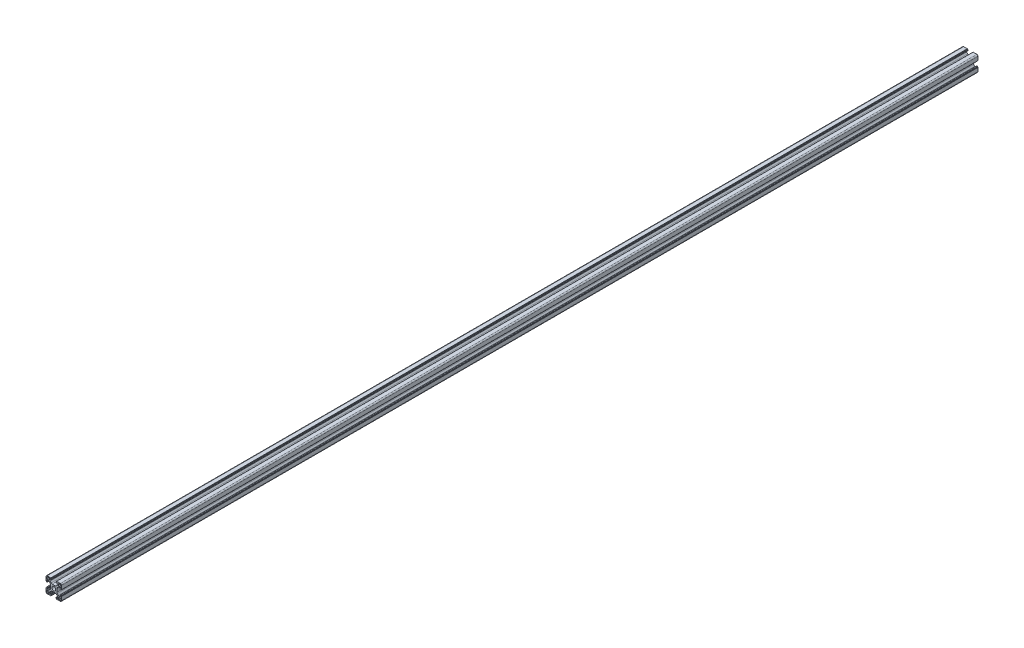
SolidWorks part; units mm, degrees
ref_plane "Спереди" through (0, 0, 0) normal (0, 0, 1) x (1, 0, 0)
ref_plane "Сверху" through (0, 0, 0) normal (0, 1, 0) x (1, 0, 0)
ref_plane "Справа" through (0, 0, 0) normal (1, 0, 0) x (0, 0, -1)
sketch "Эскиз1" plane through (0, 0, 0) normal (0, 0, 1) x (1, 0, 0)
  line L0 (-25.8933, 69.2728) -> (-28.8933, 66.2728) construction
  line L1 (-34.9933, 64.1728) -> (-33.0945, 64.1728)
  line L2 (-34.9933, 60.1728) -> (-24.9933, 70.1728) construction
  line L3 (-27.3933, 67.7728) -> (-28.8933, 69.2728) construction
  line L4 (-31.6803, 64.7586) -> (-30.3791, 66.0598)
  line L5 (-28.0933, 66.2728) -> (-26.6933, 66.2728)
  line L6 (-28.8933, 67.0728) -> (-28.8933, 68.4728)
  line L7 (-26.6933, 69.2728) -> (-28.0933, 69.2728)
  line L8 (-29.7933, 68.3728) -> (-29.7933, 67.474)
  line L9 (-31.2301, 68.246) -> (-30.7498, 68.7264)
  line L10 (-31.7933, 69.7219) -> (-31.2933, 69.7219)
  line L11 (-31.4069, 68.1728) -> (-31.6933, 68.1728)
  line L12 (-30.3962, 68.8728) -> (-30.2933, 68.8728)
  line L13 (-31.2933, 70.0228) -> (-31.2933, 69.7219)
  line L14 (-31.9433, 69.5719) -> (-31.9433, 68.4228)
  line L15 (-26.4933, 70.1728) -> (-31.1433, 70.1728)
  line L16 (-25.8933, 68.4728) -> (-25.8933, 67.0728)
  line L17 (-24.9933, 68.6728) -> (-24.9933, 64.0228)
  line L18 (-25.5943, 63.2228) -> (-26.7433, 63.2228)
  line L19 (-25.1433, 63.8728) -> (-25.4443, 63.8728)
  line L20 (-26.2933, 64.7699) -> (-26.2933, 64.8728)
  line L21 (-26.9933, 63.7592) -> (-26.9933, 63.4728)
  line L22 (-25.4443, 63.3728) -> (-25.4443, 63.8728)
  line L23 (-26.9201, 63.936) -> (-26.4398, 64.4164)
  line L24 (-26.7933, 65.3728) -> (-27.6921, 65.3728)
  line L25 (-30.4075, 63.4858) -> (-29.1063, 64.787)
  line L26 (-30.9933, 60.1728) -> (-30.9933, 62.0716)
  line L27 (-30.9933, 60.1728) -> (-30.9933, 58.274)
  line L28 (-30.4075, 56.8598) -> (-29.1063, 55.5586)
  line L29 (-28.8933, 53.2728) -> (-28.8933, 51.8728)
  line L30 (-28.0933, 54.0728) -> (-26.6933, 54.0728)
  line L31 (-25.8933, 51.8728) -> (-25.8933, 53.2728)
  line L32 (-26.7933, 54.9728) -> (-27.6921, 54.9728)
  line L33 (-26.9201, 56.4096) -> (-26.4398, 55.9292)
  line L34 (-25.4443, 56.9728) -> (-25.4443, 56.4728)
  line L35 (-26.9933, 56.5864) -> (-26.9933, 56.8728)
  line L36 (-26.2933, 55.5757) -> (-26.2933, 55.4728)
  line L37 (-25.1433, 56.4728) -> (-25.4443, 56.4728)
  line L38 (-25.5943, 57.1228) -> (-26.7433, 57.1228)
  line L39 (-24.9933, 51.6728) -> (-24.9933, 56.3228)
  line L40 (-26.6933, 51.0728) -> (-28.0933, 51.0728)
  line L41 (-26.4933, 50.1728) -> (-31.1433, 50.1728)
  line L42 (-31.9433, 50.7737) -> (-31.9433, 51.9228)
  line L43 (-31.2933, 50.3228) -> (-31.2933, 50.6237)
  line L44 (-30.3962, 51.4728) -> (-30.2933, 51.4728)
  line L45 (-31.4069, 52.1728) -> (-31.6933, 52.1728)
  line L46 (-31.7933, 50.6237) -> (-31.2933, 50.6237)
  line L47 (-31.2301, 52.0996) -> (-30.7498, 51.6192)
  line L48 (-29.7933, 51.9728) -> (-29.7933, 52.8716)
  line L49 (-31.6803, 55.587) -> (-30.3791, 54.2858)
  line L50 (-34.9933, 56.1728) -> (-33.0945, 56.1728)
  line L51 (-25.8933, 51.0728) -> (-28.8933, 54.0728) construction
  line L52 (-34.9933, 60.1728) -> (-24.9933, 50.1728) construction
  line L53 (-27.3933, 52.5728) -> (-25.8933, 54.0728) construction
  line L54 (-34.9933, 56.1728) -> (-36.8921, 56.1728)
  line L55 (-38.3063, 55.587) -> (-39.6075, 54.2858)
  line L56 (-41.8933, 54.0728) -> (-43.2933, 54.0728)
  line L57 (-41.0933, 53.2728) -> (-41.0933, 51.8728)
  line L58 (-43.2933, 51.0728) -> (-41.8933, 51.0728)
  line L59 (-40.1933, 51.9728) -> (-40.1933, 52.8716)
  line L60 (-38.7565, 52.0996) -> (-39.2369, 51.6192)
  line L61 (-38.1933, 50.6237) -> (-38.6933, 50.6237)
  line L62 (-38.5798, 52.1728) -> (-38.2933, 52.1728)
  line L63 (-39.5904, 51.4728) -> (-39.6933, 51.4728)
  line L64 (-38.6933, 50.3228) -> (-38.6933, 50.6237)
  line L65 (-38.0433, 50.7737) -> (-38.0433, 51.9228)
  line L66 (-43.4933, 50.1728) -> (-38.8433, 50.1728)
  line L67 (-44.0933, 51.8728) -> (-44.0933, 53.2728)
  line L68 (-44.9933, 51.6728) -> (-44.9933, 56.3228)
  line L69 (-44.3924, 57.1228) -> (-43.2433, 57.1228)
  line L70 (-44.8433, 56.4728) -> (-44.5424, 56.4728)
  line L71 (-43.6933, 55.5757) -> (-43.6933, 55.4728)
  line L72 (-42.9933, 56.5864) -> (-42.9933, 56.8728)
  line L73 (-44.5424, 56.9728) -> (-44.5424, 56.4728)
  line L74 (-43.0665, 56.4096) -> (-43.5469, 55.9292)
  line L75 (-43.1933, 54.9728) -> (-42.2945, 54.9728)
  line L76 (-39.5791, 56.8598) -> (-40.8803, 55.5586)
  line L77 (-38.9933, 60.1728) -> (-38.9933, 58.274)
  line L78 (-44.0933, 51.0728) -> (-41.0933, 54.0728) construction
  line L79 (-34.9933, 60.1728) -> (-44.9933, 50.1728) construction
  line L80 (-42.5933, 52.5728) -> (-41.0933, 51.0728) construction
  line L81 (-38.9933, 60.1728) -> (-38.9933, 62.0716)
  line L82 (-39.5791, 63.4858) -> (-40.8803, 64.787)
  line L83 (-41.0933, 67.0728) -> (-41.0933, 68.4728)
  line L84 (-41.8933, 66.2728) -> (-43.2933, 66.2728)
  line L85 (-44.0933, 68.4728) -> (-44.0933, 67.0728)
  line L86 (-43.1933, 65.3728) -> (-42.2945, 65.3728)
  line L87 (-43.0665, 63.936) -> (-43.5469, 64.4164)
  line L88 (-44.5424, 63.3728) -> (-44.5424, 63.8728)
  line L89 (-42.9933, 63.7592) -> (-42.9933, 63.4728)
  line L90 (-43.6933, 64.7699) -> (-43.6933, 64.8728)
  line L91 (-44.8433, 63.8728) -> (-44.5424, 63.8728)
  line L92 (-44.3924, 63.2228) -> (-43.2433, 63.2228)
  line L93 (-44.9933, 68.6728) -> (-44.9933, 64.0228)
  line L94 (-43.2933, 69.2728) -> (-41.8933, 69.2728)
  line L95 (-43.4933, 70.1728) -> (-38.8433, 70.1728)
  line L96 (-38.0433, 69.5719) -> (-38.0433, 68.4228)
  line L97 (-38.6933, 70.0228) -> (-38.6933, 69.7219)
  line L98 (-39.5904, 68.8728) -> (-39.6933, 68.8728)
  line L99 (-38.5798, 68.1728) -> (-38.2933, 68.1728)
  line L100 (-38.1933, 69.7219) -> (-38.6933, 69.7219)
  line L101 (-38.7565, 68.246) -> (-39.2369, 68.7264)
  line L102 (-40.1933, 68.3728) -> (-40.1933, 67.474)
  line L103 (-38.3063, 64.7586) -> (-39.6075, 66.0598)
  line L104 (-34.9933, 64.1728) -> (-36.8921, 64.1728)
  line L105 (-46.7574, 60.1728) -> (-23.489, 60.1728) construction
  line L106 (-44.0933, 69.2728) -> (-41.0933, 66.2728) construction
  line L107 (-34.9933, 48.0864) -> (-34.9933, 70.8917) construction
  line L108 (-34.9933, 60.1728) -> (-44.9933, 70.1728) construction
  line L109 (-42.5933, 67.7728) -> (-44.0933, 66.2728) construction
  arc A0 (-25.8933, 68.4728) -> (-26.6933, 69.2728) centre (-26.6933, 68.4728) ccw
  arc A1 (-28.0933, 69.2728) -> (-28.8933, 68.4728) centre (-28.0933, 68.4728) ccw
  arc A2 (-28.0933, 66.2728) -> (-28.8933, 67.0728) centre (-28.0933, 67.0728) cw
  arc A3 (-26.4933, 70.1728) -> (-24.9933, 68.6728) centre (-26.4933, 68.6728) cw
  arc A4 (-31.7933, 69.7219) -> (-31.9433, 69.5719) centre (-31.7933, 69.5719) ccw
  arc A5 (-31.1433, 70.1728) -> (-31.2933, 70.0228) centre (-31.1433, 70.0228) ccw
  arc A6 (-31.4069, 68.1728) -> (-31.2301, 68.246) centre (-31.4069, 68.4228) ccw
  arc A7 (-31.6933, 68.1728) -> (-31.9433, 68.4228) centre (-31.6933, 68.4228) cw
  arc A8 (-30.7498, 68.7264) -> (-30.3962, 68.8728) centre (-30.3962, 68.3728) cw
  arc A9 (-30.2933, 68.8728) -> (-29.7933, 68.3728) centre (-30.2933, 68.3728) cw
  arc A10 (-32.4933, 60.1728) -> (-34.9933, 62.6728) centre (-34.9933, 60.1728) ccw
  arc A11 (-33.0945, 64.1728) -> (-31.6803, 64.7586) centre (-33.0945, 66.1728) ccw
  arc A12 (-29.7933, 67.474) -> (-30.3791, 66.0598) centre (-31.7933, 67.474) cw
  arc A13 (-25.8933, 67.0728) -> (-26.6933, 66.2728) centre (-26.6933, 67.0728) cw
  arc A14 (-26.2933, 64.8728) -> (-26.7933, 65.3728) centre (-26.7933, 64.8728) ccw
  arc A15 (-26.4398, 64.4164) -> (-26.2933, 64.7699) centre (-26.7933, 64.7699) ccw
  arc A16 (-26.9933, 63.4728) -> (-26.7433, 63.2228) centre (-26.7433, 63.4728) ccw
  arc A17 (-26.9933, 63.7592) -> (-26.9201, 63.936) centre (-26.7433, 63.7592) cw
  arc A18 (-24.9933, 64.0228) -> (-25.1433, 63.8728) centre (-25.1433, 64.0228) cw
  arc A19 (-25.4443, 63.3728) -> (-25.5943, 63.2228) centre (-25.5943, 63.3728) cw
  arc A20 (-27.6921, 65.3728) -> (-29.1063, 64.787) centre (-27.6921, 63.3728) ccw
  arc A21 (-30.9933, 62.0716) -> (-30.4075, 63.4858) centre (-28.9933, 62.0716) cw
  arc A22 (-26.6933, 51.0728) -> (-25.8933, 51.8728) centre (-26.6933, 51.8728) ccw
  arc A23 (-25.8933, 53.2728) -> (-26.6933, 54.0728) centre (-26.6933, 53.2728) ccw
  arc A24 (-28.8933, 53.2728) -> (-28.0933, 54.0728) centre (-28.0933, 53.2728) cw
  arc A25 (-24.9933, 51.6728) -> (-26.4933, 50.1728) centre (-26.4933, 51.6728) cw
  arc A26 (-25.4443, 56.9728) -> (-25.5943, 57.1228) centre (-25.5943, 56.9728) ccw
  arc A27 (-24.9933, 56.3228) -> (-25.1433, 56.4728) centre (-25.1433, 56.3228) ccw
  arc A28 (-26.9933, 56.5864) -> (-26.9201, 56.4096) centre (-26.7433, 56.5864) ccw
  arc A29 (-26.9933, 56.8728) -> (-26.7433, 57.1228) centre (-26.7433, 56.8728) cw
  arc A30 (-26.4398, 55.9292) -> (-26.2933, 55.5757) centre (-26.7933, 55.5757) cw
  arc A31 (-26.2933, 55.4728) -> (-26.7933, 54.9728) centre (-26.7933, 55.4728) cw
  arc A32 (-34.9933, 57.6728) -> (-32.4933, 60.1728) centre (-34.9933, 60.1728) ccw
  arc A33 (-30.9933, 58.274) -> (-30.4075, 56.8598) centre (-28.9933, 58.274) ccw
  arc A34 (-27.6921, 54.9728) -> (-29.1063, 55.5586) centre (-27.6921, 56.9728) cw
  arc A35 (-28.0933, 51.0728) -> (-28.8933, 51.8728) centre (-28.0933, 51.8728) cw
  arc A36 (-30.2933, 51.4728) -> (-29.7933, 51.9728) centre (-30.2933, 51.9728) ccw
  arc A37 (-30.7498, 51.6192) -> (-30.3962, 51.4728) centre (-30.3962, 51.9728) ccw
  arc A38 (-31.6933, 52.1728) -> (-31.9433, 51.9228) centre (-31.6933, 51.9228) ccw
  arc A39 (-31.4069, 52.1728) -> (-31.2301, 52.0996) centre (-31.4069, 51.9228) cw
  arc A40 (-31.1433, 50.1728) -> (-31.2933, 50.3228) centre (-31.1433, 50.3228) cw
  arc A41 (-31.7933, 50.6237) -> (-31.9433, 50.7737) centre (-31.7933, 50.7737) cw
  arc A42 (-29.7933, 52.8716) -> (-30.3791, 54.2858) centre (-31.7933, 52.8716) ccw
  arc A43 (-33.0945, 56.1728) -> (-31.6803, 55.587) centre (-33.0945, 54.1728) cw
  arc A44 (-44.0933, 51.8728) -> (-43.2933, 51.0728) centre (-43.2933, 51.8728) ccw
  arc A45 (-41.8933, 51.0728) -> (-41.0933, 51.8728) centre (-41.8933, 51.8728) ccw
  arc A46 (-41.8933, 54.0728) -> (-41.0933, 53.2728) centre (-41.8933, 53.2728) cw
  arc A47 (-43.4933, 50.1728) -> (-44.9933, 51.6728) centre (-43.4933, 51.6728) cw
  arc A48 (-38.1933, 50.6237) -> (-38.0433, 50.7737) centre (-38.1933, 50.7737) ccw
  arc A49 (-38.8433, 50.1728) -> (-38.6933, 50.3228) centre (-38.8433, 50.3228) ccw
  arc A50 (-38.5798, 52.1728) -> (-38.7565, 52.0996) centre (-38.5798, 51.9228) ccw
  arc A51 (-38.2933, 52.1728) -> (-38.0433, 51.9228) centre (-38.2933, 51.9228) cw
  arc A52 (-39.2369, 51.6192) -> (-39.5904, 51.4728) centre (-39.5904, 51.9728) cw
  arc A53 (-39.6933, 51.4728) -> (-40.1933, 51.9728) centre (-39.6933, 51.9728) cw
  arc A54 (-37.4933, 60.1728) -> (-34.9933, 57.6728) centre (-34.9933, 60.1728) ccw
  arc A55 (-36.8921, 56.1728) -> (-38.3063, 55.587) centre (-36.8921, 54.1728) ccw
  arc A56 (-40.1933, 52.8716) -> (-39.6075, 54.2858) centre (-38.1933, 52.8716) cw
  arc A57 (-44.0933, 53.2728) -> (-43.2933, 54.0728) centre (-43.2933, 53.2728) cw
  arc A58 (-43.6933, 55.4728) -> (-43.1933, 54.9728) centre (-43.1933, 55.4728) ccw
  arc A59 (-43.5469, 55.9292) -> (-43.6933, 55.5757) centre (-43.1933, 55.5757) ccw
  arc A60 (-42.9933, 56.8728) -> (-43.2433, 57.1228) centre (-43.2433, 56.8728) ccw
  arc A61 (-42.9933, 56.5864) -> (-43.0665, 56.4096) centre (-43.2433, 56.5864) cw
  arc A62 (-44.9933, 56.3228) -> (-44.8433, 56.4728) centre (-44.8433, 56.3228) cw
  arc A63 (-44.5424, 56.9728) -> (-44.3924, 57.1228) centre (-44.3924, 56.9728) cw
  arc A64 (-42.2945, 54.9728) -> (-40.8803, 55.5586) centre (-42.2945, 56.9728) ccw
  arc A65 (-38.9933, 58.274) -> (-39.5791, 56.8598) centre (-40.9933, 58.274) cw
  arc A66 (-43.2933, 69.2728) -> (-44.0933, 68.4728) centre (-43.2933, 68.4728) ccw
  arc A67 (-44.0933, 67.0728) -> (-43.2933, 66.2728) centre (-43.2933, 67.0728) ccw
  arc A68 (-41.0933, 67.0728) -> (-41.8933, 66.2728) centre (-41.8933, 67.0728) cw
  arc A69 (-44.9933, 68.6728) -> (-43.4933, 70.1728) centre (-43.4933, 68.6728) cw
  arc A70 (-44.5424, 63.3728) -> (-44.3924, 63.2228) centre (-44.3924, 63.3728) ccw
  arc A71 (-44.9933, 64.0228) -> (-44.8433, 63.8728) centre (-44.8433, 64.0228) ccw
  arc A72 (-42.9933, 63.7592) -> (-43.0665, 63.936) centre (-43.2433, 63.7592) ccw
  arc A73 (-42.9933, 63.4728) -> (-43.2433, 63.2228) centre (-43.2433, 63.4728) cw
  arc A74 (-43.5469, 64.4164) -> (-43.6933, 64.7699) centre (-43.1933, 64.7699) cw
  arc A75 (-43.6933, 64.8728) -> (-43.1933, 65.3728) centre (-43.1933, 64.8728) cw
  arc A76 (-34.9933, 62.6728) -> (-37.4933, 60.1728) centre (-34.9933, 60.1728) ccw
  arc A77 (-38.9933, 62.0716) -> (-39.5791, 63.4858) centre (-40.9933, 62.0716) ccw
  arc A78 (-42.2945, 65.3728) -> (-40.8803, 64.787) centre (-42.2945, 63.3728) cw
  arc A79 (-41.8933, 69.2728) -> (-41.0933, 68.4728) centre (-41.8933, 68.4728) cw
  arc A80 (-39.6933, 68.8728) -> (-40.1933, 68.3728) centre (-39.6933, 68.3728) ccw
  arc A81 (-39.2369, 68.7264) -> (-39.5904, 68.8728) centre (-39.5904, 68.3728) ccw
  arc A82 (-38.2933, 68.1728) -> (-38.0433, 68.4228) centre (-38.2933, 68.4228) ccw
  arc A83 (-38.5798, 68.1728) -> (-38.7565, 68.246) centre (-38.5798, 68.4228) cw
  arc A84 (-38.8433, 70.1728) -> (-38.6933, 70.0228) centre (-38.8433, 70.0228) cw
  arc A85 (-38.1933, 69.7219) -> (-38.0433, 69.5719) centre (-38.1933, 69.5719) cw
  arc A86 (-40.1933, 67.474) -> (-39.6075, 66.0598) centre (-38.1933, 67.474) ccw
  arc A87 (-36.8921, 64.1728) -> (-38.3063, 64.7586) centre (-36.8921, 66.1728) cw
  point P0 (-34.9933, 60.1728)
  point P9 (-34.9933, 60.1728)
  point P40 (-26.2933, 63.8728)
  point P93 (-31.2933, 51.4728)
  point P144 (-31.2933, 68.8728)
  point P152 (-26.2933, 56.4728)
  point P153 (-34.9933, 56.2485)
  point P154 (-34.9933, 60.1728)
  point P189 (-43.6933, 56.4728)
  point P228 (-38.6933, 51.4728)
  point P229 (-38.9176, 60.1728)
  point P230 (-34.9933, 60.1728)
  point P268 (-38.6933, 68.8728)
  point P273 (-31.0691, 60.1728)
  point P306 (-43.6933, 63.8728)
  point P307 (-34.9933, 64.0971)
  point P309 (-34.9933, 60.1728)
  dimension "D3" = 5
  dimension "D6" = 2
  dimension "D1" = 2
  dimension "D2" = 6
  dimension "D4" = 4
  dimension "D5" = 0.9
extrude "Бобышка-Вытянуть1" add sketch "Эскиз1" along normal blind 1180
